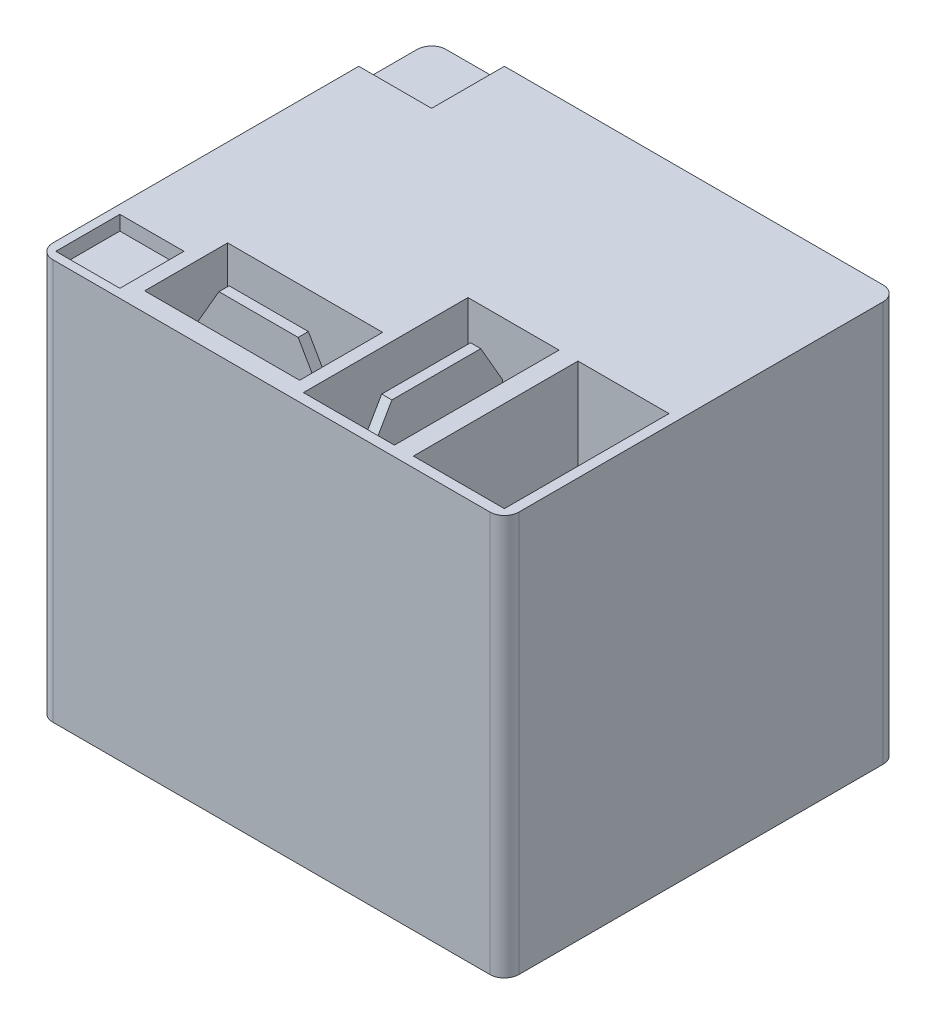
SolidWorks part; units mm, degrees
ref_plane "Front Plane" through (0, 0, 0) normal (0, 0, 1) x (1, 0, 0)
ref_plane "Top Plane" through (0, 0, 0) normal (0, 1, 0) x (1, 0, 0)
ref_plane "Right Plane" through (0, 0, 0) normal (1, 0, 0) x (0, 0, -1)
sketch "Sketch1" plane through (0, 0, 0) normal (0, 1, 0) x (1, 0, 0)
  line L1 (0, 0) -> (32, 0)
  line L2 (0, 0) -> (0, 27)
  line L3 (0, 27) -> (32, 27)
  line L4 (32, 0) -> (32, 27)
  dimension "D1" = 32
  dimension "D2" = 27
extrude "Boss-Extrude1" add sketch "Sketch1" along normal blind 27.5
sketch "Sketch2" plane through (0, 27.5, 0) normal (0, 1, 0) x (1, 0, 0)
  line L0 (0, 0) -> (32, 0) construction
  line L1 (6, 7) -> (16.64, 7)
  line L2 (6, 7) -> (6, 1.3)
  line L3 (6, 1.3) -> (16.64, 1.3)
  line L4 (16.64, 7) -> (16.64, 1.3)
  line L5 (17.5, 12) -> (23.75, 12)
  line L6 (17.5, 12) -> (17.5, 0.7)
  line L7 (17.5, 0.7) -> (23.75, 0.7)
  line L8 (23.75, 12) -> (23.75, 0.7)
  line L9 (25.05, 12) -> (31.3, 12)
  line L10 (25.05, 12) -> (25.05, 0.7)
  line L11 (25.05, 0.7) -> (31.3, 0.7)
  line L12 (31.3, 12) -> (31.3, 0.7)
  line L13 (32, 0) -> (32, 27) construction
  line L14 (0, 27) -> (0, 0) construction
  line L15 (32, 27) -> (0, 27) construction
  dimension "D1" = 1.3
  dimension "D2" = 0.7
  dimension "D3" = 0.7
  dimension "D4" = 6.25
  dimension "D5" = 6.25
  dimension "D6" = 1.3
  dimension "D7" = 0.86
  dimension "D8" = 6
  dimension "D9" = 15
  dimension "D10" = 20
extrude "Cut-Extrude1" cut sketch "Sketch2" against normal blind 9.3
sketch "Sketch3" plane through (0, 27.5, 0) normal (0, 1, 0) x (1, 0, 0)
  line L0 (0, 0) -> (32, 0) construction
  line L1 (0.6, 0.6) -> (5, 0.6)
  line L2 (0.6, 0.6) -> (0.6, 5)
  line L3 (0.6, 5) -> (5, 5)
  line L4 (5, 0.6) -> (5, 5)
  line L5 (0, 27) -> (0, 0) construction
  line L6 (6, 7) -> (6, 1.3) construction
  line L8 (0, 27) -> (5, 27)
  line L9 (0, 27) -> (0, 22)
  line L10 (0, 22) -> (5, 22)
  line L11 (5, 27) -> (5, 22)
  dimension "D1" = 0.6
  dimension "D2" = 0.6
  dimension "D3" = 1
  dimension "D4" = 5
extrude "Cut-Extrude2" cut sketch "Sketch3" against normal blind 1
sketch "Sketch4" plane through (0, 18.2, 0) normal (0, 1, 0) x (1, 0, 0)
  line L0 (16.64, 1.3) -> (16.64, 7) construction
  line L1 (7.1, 3.8) -> (15.54, 3.8)
  line L2 (7.1, 3.8) -> (7.1, 4.5)
  line L3 (7.1, 4.5) -> (15.54, 4.5)
  line L4 (15.54, 3.8) -> (15.54, 4.5)
  line L5 (16.64, 7) -> (6, 7) construction
  line L6 (16.64, 1.3) -> (16.64, 7) construction
  line L7 (6, 7) -> (6, 1.3) construction
  line L8 (23.75, 12) -> (17.5, 12) construction
  line L9 (20.275, 10.9) -> (20.975, 10.9)
  line L10 (20.275, 10.9) -> (20.275, 1.8)
  line L11 (20.275, 1.8) -> (20.975, 1.8)
  line L12 (20.975, 10.9) -> (20.975, 1.8)
  line L13 (17.5, 12) -> (17.5, 0.7) construction
  line L14 (17.5, 0.7) -> (23.75, 0.7) construction
  point P6 (16.64, 4.15)
  point P7 (15.54, 4.15)
  point P10 (11.32, 7)
  point P11 (11.32, 4.5)
  point P22 (20.625, 12)
  point P23 (20.625, 10.9)
  point P26 (17.5, 6.35)
  point P27 (20.275, 6.35)
  dimension "D1" = 0.7
  dimension "D2" = 1.1
  dimension "D3" = 1.1
  dimension "D4" = 0.7
  dimension "D5" = 1.1
extrude "Boss-Extrude2" add sketch "Sketch4" along normal up to surface (9.3 mm away) separate body up to face at (2.8, 27.5, -2.8)
chamfer "Chamfer1" distance 1.5 angle 60 2 edges at (15.54, 27.5, -4.15) (7.1, 27.5, -4.15)
chamfer "Chamfer2" distance 1.5 angle 60 2 edges at (20.625, 27.5, -10.9) (20.625, 27.5, -1.8)
fillet "Fillet1" radius 1 4 edges at (0, 13.25, -27) (32, 13.75, -27) (32, 13.75, 0) (0, 13.75, 0)
sketch "Sketch5" plane through (0, 0, 0) normal (0, -1, 0) x (1, 0, 0)
  line L0 (31, -27) -> (5, -27) construction
  line L1 (0, -22) -> (0, -1) construction
  line L2 (1, 0) -> (31, 0) construction
  line L3 (32, -1) -> (32, -26) construction
  circle A0 centre (5.7, -19.6) radius 0.35
  circle A1 centre (5.7, -10) radius 0.35
  circle A2 centre (19, -24) radius 0.6
  circle A3 centre (21.5, -5.3) radius 0.6
  dimension "D3" = 0.7
  dimension "D6" = 1.2
  dimension "D1" = 7.4
  dimension "D2" = 5.7
  dimension "D4" = 5.7
  dimension "D5" = 10
  dimension "D7" = 3
  dimension "D8" = 13
  dimension "D9" = 10.5
  dimension "D10" = 5.3
extrude "Boss-Extrude3" add sketch "Sketch5" along normal blind 4.25 separate body
